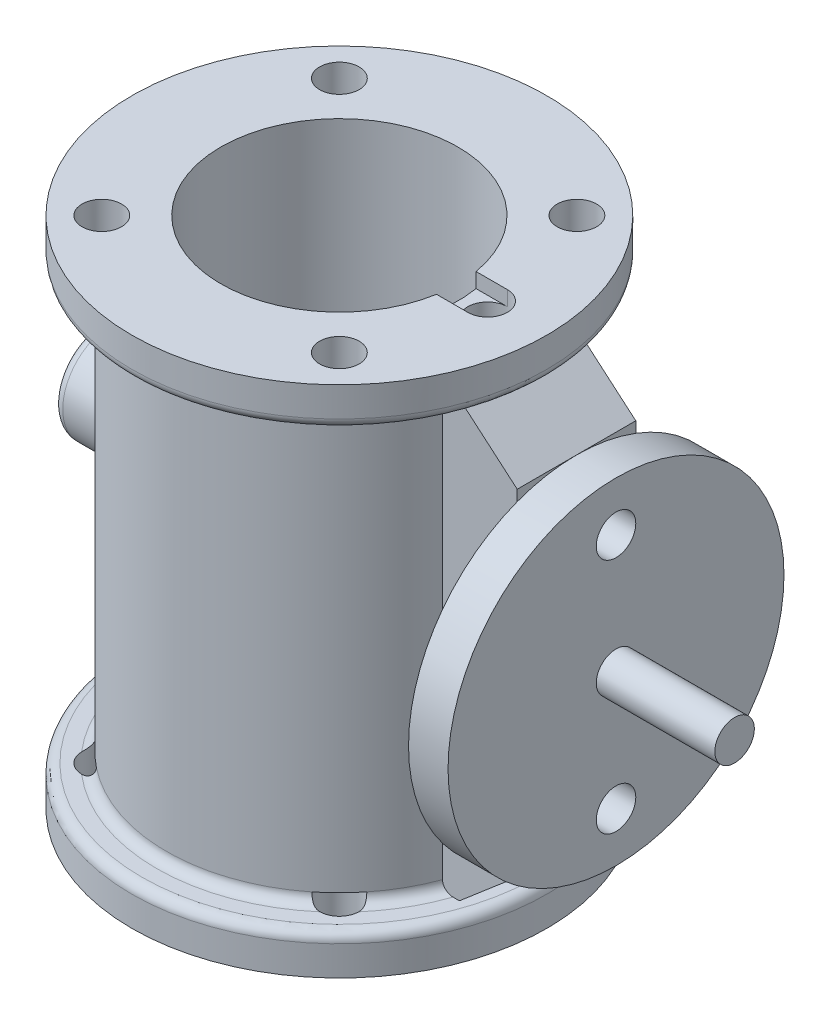
SolidWorks part; units mm, degrees
ref_plane "Front Plane" through (0, 0, 0) normal (0, 0, 1) x (1, 0, 0)
ref_plane "Top Plane" through (0, 0, 0) normal (0, 1, 0) x (1, 0, 0)
ref_plane "Right Plane" through (0, 0, 0) normal (1, 0, 0) x (0, 0, -1)
sketch "Sketch1" plane through (0, 0, 0) normal (0, 0, 1) x (1, 0, 0)
  line L0 (0, 26) -> (0, -26) construction
  line L1 (-21, 26) -> (-12, 26)
  line L2 (-12, 26) -> (-12, -26)
  line L3 (-12, -26) -> (-21, -26)
  line L4 (-21, -26) -> (-21, -22)
  line L5 (-21, -22) -> (-18.5, -22)
  line L6 (-17.5, -21) -> (-17.5, 21)
  line L7 (-18.5, 22) -> (-21, 22)
  line L8 (-21, 22) -> (-21, 26)
  arc A0 (-18.5, -22) -> (-17.5, -21) centre (-18.5, -21) ccw
  arc A1 (-17.5, 21) -> (-18.5, 22) centre (-18.5, 21) ccw
  point P4 (0, 0)
  dimension "D6" = 1
  dimension "D1" = 52
  dimension "D2" = 12
  dimension "D3" = 17.5
  dimension "D4" = 4
  dimension "D5" = 21
revolve "Revolve1" add sketch "Sketch1" angle 360 about L0
sketch "Sketch2" plane through (0, 26, 0) normal (0, 1, 0) x (1, 0, 0)
  line L0 (0, 0) -> (0, 21) construction
  line L1 (0, 0) -> (14.8492, 14.8492) construction
  circle A0 centre (0, 0) radius 17 construction
  circle A1 centre (12.0208, 12.0208) radius 2
  circle A2 centre (0, 0) radius 21 construction
  dimension "D1" = 34
  dimension "D2" = 4
  dimension "D3" = 45
extrude "Cut-Extrude1" cut sketch "Sketch2" against normal blind 5
pattern_circular "CirPattern1" count 4 over 360 about axis through (0, 0, 0) along (0, 1, 0) of "Cut-Extrude1"
mirror "Mirror1" about plane through (0, 0, 0) normal (0, 1, 0) of "CirPattern1", "Cut-Extrude1"
sketch "Sketch3" plane through (0, 0, 0) normal (1, 0, 0) x (0, 0, -1)
  circle A0 centre (0, 0) radius 5
  dimension "D1" = 10
extrude "Boss-Extrude1" add sketch "Sketch3" against normal blind 11 from offset 13 offset against normal yes
fillet "Fillet1" radius 1 2 edges at (-16.7962, 0.9293, 4.9129) (-24, 0, -5)
sketch "Sketch4" plane through (0, 0, 0) normal (0, 0, 1) x (1, 0, 0)
  line L0 (-24, 0) -> (-22, 0)
  line L1 (-24, 4) -> (-24, -4) construction
  line L2 (-22, 0) -> (-24, 2)
  line L3 (-24, 2) -> (-24, 0)
  dimension "D1" = 2
  dimension "D2" = 45
revolve "Cut-Revolve1" cut sketch "Sketch4" angle 360 about L0
sketch "Sketch5" plane through (0, 0, 0) normal (1, 0, 0) x (0, 0, -1)
  line L1 (-6, 17) -> (6, 17)
  line L2 (-6, 17) -> (-6, -17)
  line L3 (-6, -17) -> (6, -17)
  line L4 (6, 17) -> (6, -17)
  line L5 (-6, 17) -> (6, -17) construction
  line L6 (-6, -17) -> (6, 17) construction
  point P0 (0, 0)
  dimension "D1" = 12
  dimension "D2" = 34
extrude "Boss-Extrude2" add sketch "Sketch5" along normal blind 11 from offset 13
sketch "Sketch6" plane through (24, 0, 0) normal (1, 0, 0) x (0, 0, -1)
  circle A0 centre (0, 0) radius 17
  dimension "D1" = 34
extrude "Boss-Extrude3" add sketch "Sketch6" along normal blind 4
sketch "Sketch7" plane through (28, 0, 0) normal (1, 0, 0) x (0, 0, -1)
  circle A0 centre (0, 0) radius 2
  dimension "D1" = 4
extrude "Cut-Extrude2" cut sketch "Sketch7" against normal blind 12
sketch "Sketch8" plane through (0, 0, 0) normal (0, 0, 1) x (1, 0, 0)
  line L0 (15, 26) -> (15, 12)
  line L1 (0, 0) -> (0, 26) construction
  line L2 (21, 26) -> (-21, 26) construction
  line L3 (15, 12) -> (28, 12)
  line L4 (28, -17) -> (28, 17) construction
  dimension "D1" = 15
  dimension "D2" = 12
sketch "Sketch9" plane through (0, 26, 0) normal (0, 1, 0) x (1, 0, 0)
  line L0 (15, 0) -> (28, 0) construction
  circle A0 centre (15, 0) radius 2
  dimension "D1" = 4
sweep "Cut-Sweep1" cut profiles "Sketch9" path "Sketch8"
mirror "Mirror2" about plane through (0, 0, 0) normal (0, 1, 0) of "Cut-Sweep1"
sketch "Sketch10" plane through (0, 26, 0) normal (0, 1, 0) x (1, 0, 0)
  line L0 (15, 2) -> (10.6785, 2)
  line L1 (10.6785, 2) -> (10.6785, -2)
  line L2 (10.6785, -2) -> (15, -2)
  circle A0 centre (15, 0) radius 2 construction
  arc A1 (15, 2) -> (15, -2) centre (15, 0) ccw
extrude "Cut-Extrude3" cut sketch "Sketch10" against normal blind 1.5
mirror "Mirror3" about plane through (0, 0, 0) normal (0, 1, 0) of "Cut-Extrude3"
sketch "Sketch11" plane through (0, 0, 0) normal (0, 0, 1) x (1, 0, 0)
  line L0 (24, 17) -> (18.152, 22)
  line L1 (-21, 22) -> (21, 22) construction
rib "Rib1" sketch "Sketch11" sketch "Sketch11" thickness 12 extrusion direction parallel to sketch draft on no parameters "D1"=12
mirror "Mirror4" about plane through (0, 0, 0) normal (0, 1, 0) of "Rib1"
sketch "Sketch12" plane through (16, 0, 0) normal (1, 0, 0) x (0, 0, -1)
  circle A0 centre (0, 0) radius 2 construction
  circle A1 centre (0, 0) radius 2
extrude "Boss-Extrude4" add sketch "Sketch12" along normal blind 24 separate body
fillet "Fillet2" radius 1 2 edges at (0, 22, 21) (0, -22, 21)
